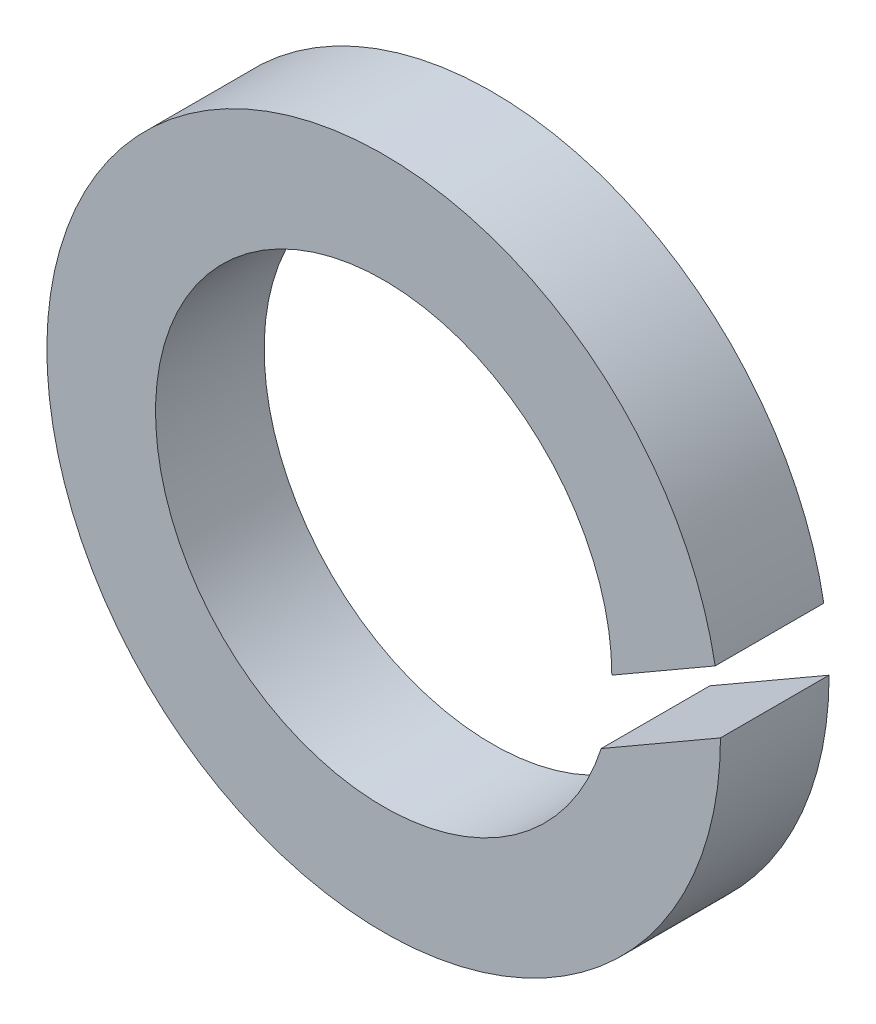
SolidWorks part; units mm, degrees
ref_plane "Спереди" through (0, 0, 0) normal (0, 0, 1) x (1, 0, 0)
ref_plane "Сверху" through (0, 0, 0) normal (0, 1, 0) x (1, 0, 0)
ref_plane "Справа" through (0, 0, 0) normal (1, 0, 0) x (0, 0, -1)
sketch "Эскиз1" plane through (0, 0, 0) normal (0, 0, 1) x (1, 0, 0)
  line L0 (0, 0) -> (2.0516, 0) construction
  line L1 (1.05, 0) -> (1.5255, 0.2745)
  line L2 (1.001, -0.317) -> (1.55, 0)
  arc A0 (1.05, 0) -> (1.001, -0.317) centre (0, 0) ccw
  arc A1 (1.5255, 0.2745) -> (1.55, 0) centre (0, 0) ccw
  dimension "D1" = 2.1
  dimension "D3" = 0.25
  dimension "D2" = 0.5
extrude "Основание-Вытянуть" add sketch "Эскиз1" along normal blind 0.5
